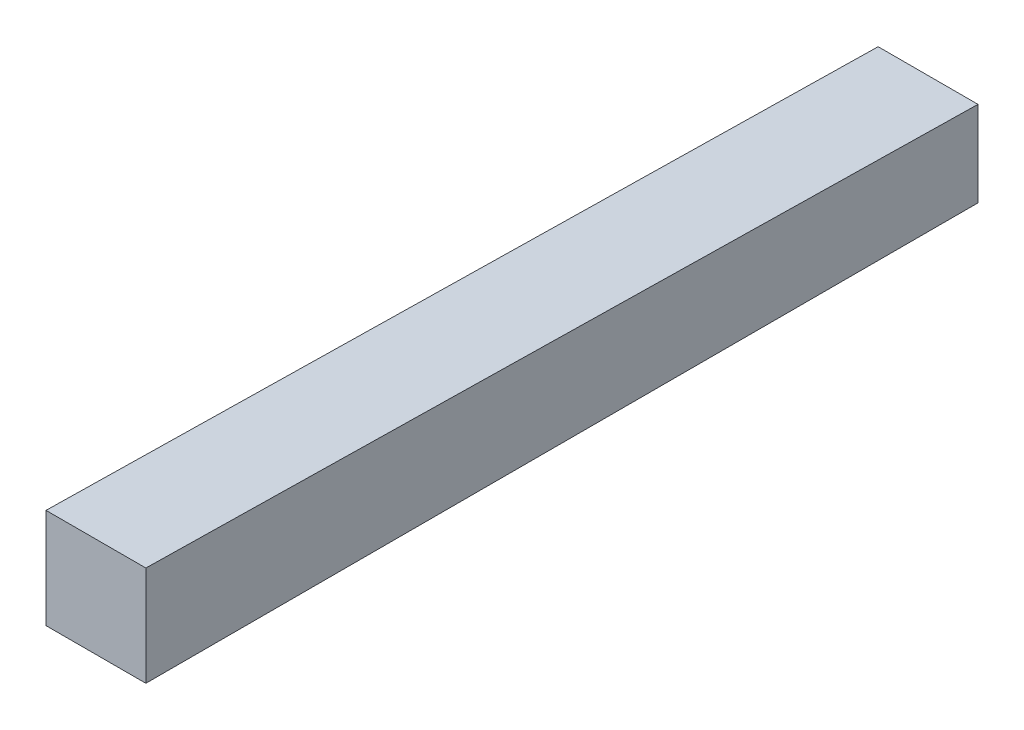
SolidWorks part; units mm, degrees
ref_plane "Front Plane" through (0, 0, 0) normal (0, 0, 1) x (1, 0, 0)
ref_plane "Top Plane" through (0, 0, 0) normal (0, 1, 0) x (1, 0, 0)
ref_plane "Right Plane" through (0, 0, 0) normal (1, 0, 0) x (0, 0, -1)
sketch "Sketch1" plane through (0, 0, 0) normal (0, 0, 1) x (1, 0, 0)
  line L1 (-3, -3) -> (3, -3)
  line L2 (-3, -3) -> (-3, 3)
  line L3 (-3, 3) -> (3, 3)
  line L4 (3, -3) -> (3, 3)
  line L5 (-3, -3) -> (3, 3) construction
  line L6 (-3, 3) -> (3, -3) construction
  point P0 (0, 0)
  dimension "D1" = 6
  dimension "D2" = 6
extrude "Boss-Extrude1" add sketch "Sketch1" along normal mid plane 50
draft "Draft1" [suppressed] type of draft neutral plane draft angle 2 faces to draft 1 parameters "D1"=2
draft "Draft2" type of draft neutral plane draft angle 1 faces to draft 1 face at (0, 3, 0) neutral plane through (0, 0, 25) neutral plane normal (0, 0, 1) reverse direction yes parameters "D1"=1
